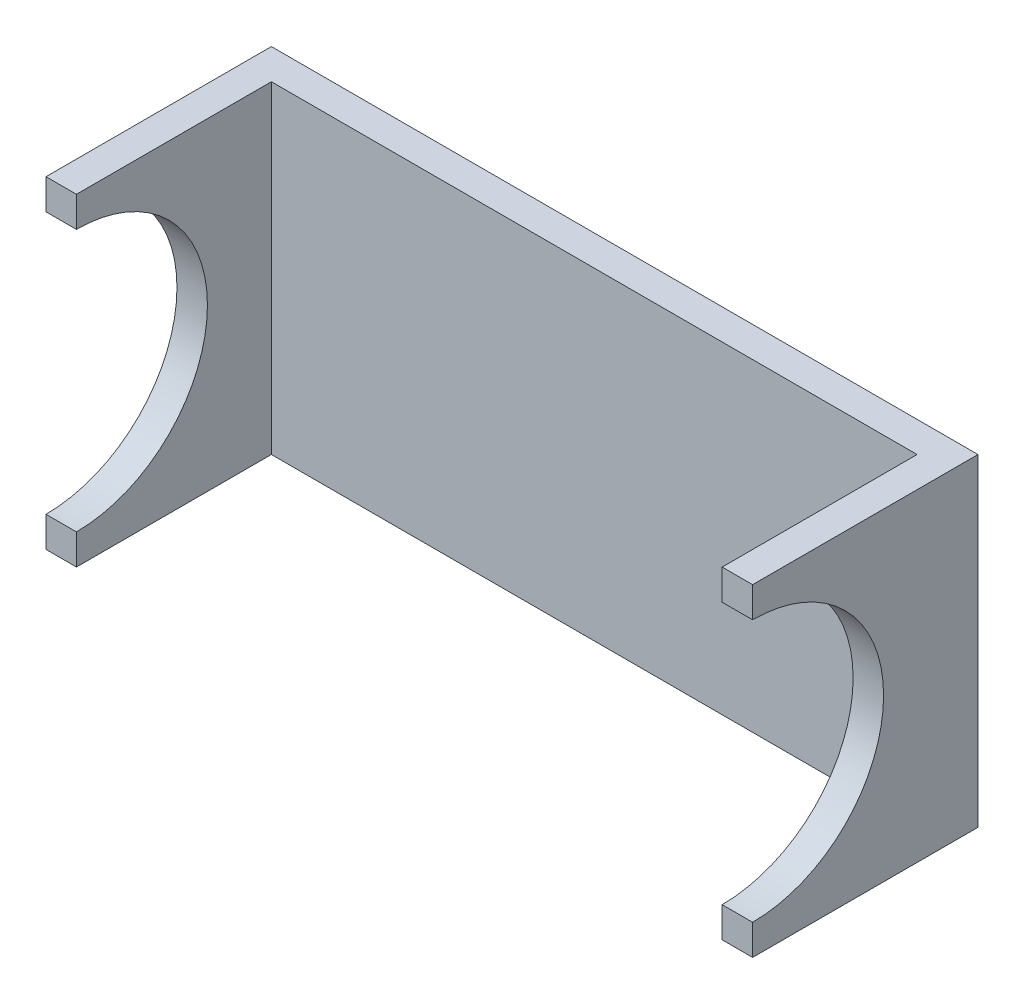
SolidWorks part; units mm, degrees
ref_plane "前视基准面" through (0, 0, 0) normal (0, 0, 1) x (1, 0, 0)
ref_plane "上视基准面" through (0, 0, 0) normal (0, 1, 0) x (1, 0, 0)
ref_plane "右视基准面" through (0, 0, 0) normal (1, 0, 0) x (0, 0, -1)
sketch "草图1" plane through (0, 0, 0) normal (0, 0, 1) x (1, 0, 0)
  line L0 (-86.7172, 0) -> (81.6201, 0) construction
  line L1 (0, 52.7846) -> (0, -54.2836) construction
  line L2 (-58, -26.5) -> (-58, 26.5)
  line L3 (-58, 26.5) -> (58, 26.5)
  line L4 (58, -26.5) -> (58, 26.5)
  line L5 (-58, -26.5) -> (58, -26.5)
  point P9 (0, 26.5)
  point P11 (58, 0)
  point P12 (-58, 0)
  dimension "D1" = 58
  dimension "D2" = 26.5
extrude "凸台-拉伸1" add sketch "草图1" along normal blind 5
sketch "草图2" plane through (0, 0, 5) normal (0, 0, 1) x (1, 0, 0)
  line L0 (-58, 26.5) -> (-58, -26.5)
  line L1 (-58, -26.5) -> (-53, -26.5)
  line L2 (-58, -26.5) -> (58, -26.5) construction
  line L3 (-53, -26.5) -> (-53, 26.5)
  line L4 (58, 26.5) -> (-58, 26.5) construction
  line L5 (-53, 26.5) -> (-58, 26.5)
  dimension "D1" = 5
extrude "凸台-拉伸2" add sketch "草图2" along normal blind 32
mirror "镜向1" about plane through (0, 0, 0) normal (1, 0, 0) of "凸台-拉伸2"
sketch "草图3" plane through (-58, 0, 0) normal (-1, 0, 0) x (0, 0, 1)
  line L0 (-12.5164, 0) -> (58.4492, 0) construction
  line L1 (37, 26.5) -> (37, -26.5) construction
  circle A0 centre (37, 0) radius 21.5
  dimension "D1" = 43
extrude "切除-拉伸1" cut sketch "草图3" against normal through all
sketch "草图4" plane through (0, 0, 0) normal (0, 0, -1) x (-1, 0, 0)
  line L0 (-70.3444, 0) -> (70.707, 0) construction
  line L1 (0, 36.5319) -> (0, -33.9937) construction
  circle A0 centre (0, 0) radius 5
  dimension "D1" = 10
extrude "凸台-拉伸3" add sketch "草图4" along normal blind 12
cosmetic thread "装饰螺纹线1" parameters "D2"=8.917
